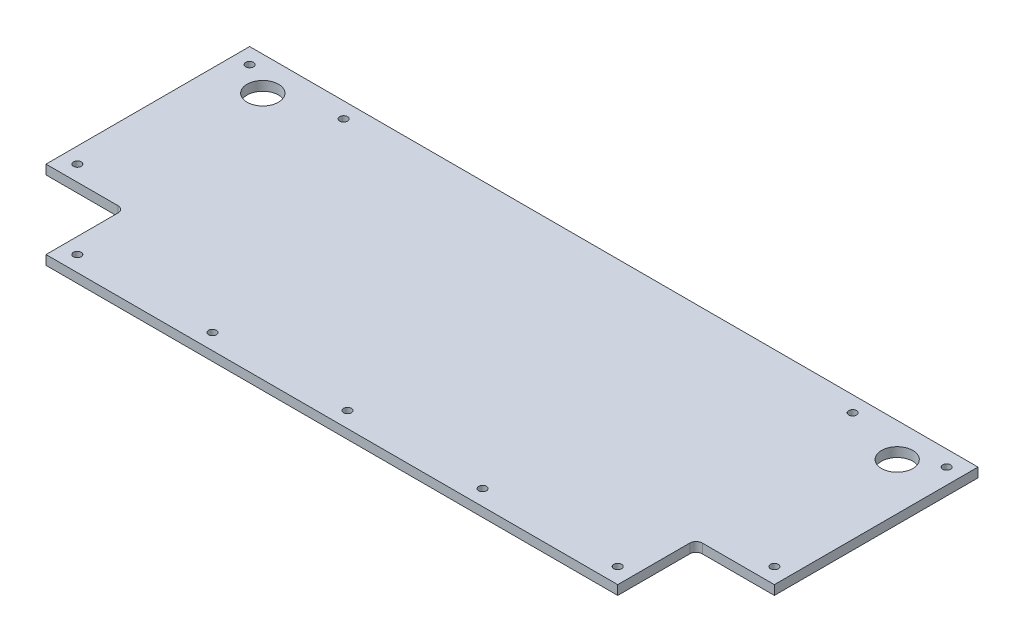
SolidWorks part; units mm, degrees
material "Acrylic (Medium-high impact)"
ref_plane "Front Plane" through (0, 0, 0) normal (0, 0, 1) x (1, 0, 0)
ref_plane "Top Plane" through (0, 0, 0) normal (0, 1, 0) x (1, 0, 0)
ref_plane "Right Plane" through (0, 0, 0) normal (1, 0, 0) x (0, 0, -1)
sketch "Sketch1" plane through (0, 0, 0) normal (0, 1, 0) x (1, 0, 0)
  line L0 (0, 0) -> (-182.5, 0)
  line L1 (-182.5, 0) -> (-182.5, 50)
  line L2 (-182.5, 50) -> (-232.5, 50)
  line L3 (-232.5, 50) -> (-232.5, 180)
  line L4 (-232.5, 180) -> (232.5, 180)
  line L5 (232.5, 180) -> (232.5, 50)
  line L6 (232.5, 50) -> (182.5, 50)
  line L7 (182.5, 50) -> (182.5, 0)
  line L8 (182.5, 0) -> (0, 0)
  dimension "D1" = 465
  dimension "D2" = 130
  dimension "D3" = 365
extrude "Boss-Extrude1" add sketch "Sketch1" along normal blind 6
sketch "Sketch2" plane through (0, 6, 0) normal (0, 1, 0) x (1, 0, 0)
  line L2 (-222.5, 170) -> (-222.5, 60) construction
  line L3 (-232.5, 180) -> (-232.5, 50) construction
  line L5 (-222.5, 170) -> (-162.5, 170) construction
  line L6 (222.5, 170) -> (222.5, 60) construction
  line L7 (222.5, 60) -> (-222.5, 60) construction
  line L8 (0, 170) -> (0, 60) construction
  line L9 (0, 60) -> (0, 0) construction
  line L10 (-232.5, 50) -> (-182.5, 50) construction
  line L11 (-172.5, 60) -> (-172.5, 10) construction
  line L12 (-172.5, 10) -> (-86.25, 10) construction
  line L13 (-86.25, 10) -> (0, 10) construction
  line L14 (0, 10) -> (86.25, 10) construction
  line L15 (86.25, 10) -> (172.5, 10) construction
  line L16 (172.5, 10) -> (172.5, 60) construction
  line L17 (-182.5, 50) -> (-182.5, 0) construction
  line L18 (-182.5, 0) -> (182.5, 0) construction
  line L19 (-162.5, 170) -> (0, 170) construction
  line L20 (0, 170) -> (162.5, 170) construction
  line L21 (162.5, 170) -> (222.5, 170) construction
  line L22 (232.5, 180) -> (-232.5, 180) construction
  circle A0 centre (-222.5, 170) radius 2.5
  circle A1 centre (-222.5, 60) radius 2.5
  circle A2 centre (222.5, 170) radius 2.5
  circle A3 centre (222.5, 60) radius 2.5
  circle A4 centre (-172.5, 10) radius 2.5
  circle A5 centre (-86.25, 10) radius 2.5
  circle A6 centre (0, 10) radius 2.5
  circle A7 centre (86.25, 10) radius 2.5
  circle A8 centre (172.5, 10) radius 2.5
  circle A9 centre (-162.5, 170) radius 2.5
  circle A10 centre (162.5, 170) radius 2.5
  dimension "D4" = 5
  dimension "D1" = 60
  dimension "D2" = 10
  dimension "D3" = 10
  dimension "D5" = 10
  dimension "D6" = 10
  dimension "D7" = 10
extrude "Cut-Extrude1" cut sketch "Sketch2" against normal through all
fillet "Fillet1" radius 4 2 edges at (-182.5, 3, -50) (182.5, 3, -50)
sketch "Sketch3" plane through (0, 6, 0) normal (0, 1, 0) x (1, 0, 0)
  line L0 (-202.5, 158.4) -> (202.5, 158.4) construction
  line L1 (202.5, 158.4) -> (232.5, 158.4) construction
  line L2 (232.5, 50) -> (232.5, 180) construction
  line L3 (-202.5, 158.4) -> (-232.5, 158.4) construction
  line L4 (-232.5, 180) -> (-232.5, 50) construction
  line L5 (232.5, 180) -> (-232.5, 180) construction
  circle A0 centre (-202.5, 158.4) radius 10
  circle A1 centre (202.5, 158.4) radius 10
  dimension "D1" = 20
  dimension "D2" = 30
  dimension "D3" = 21.6
extrude "Cut-Extrude2" cut sketch "Sketch3" against normal through all
